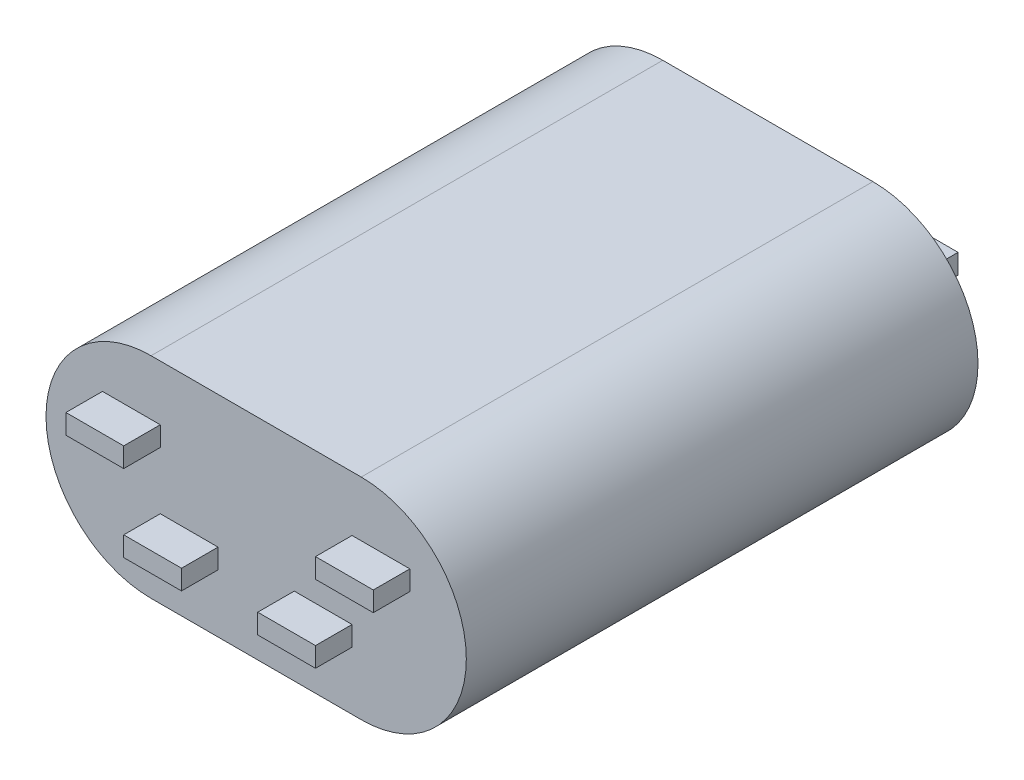
SolidWorks part; units mm, degrees
material "Cast Carbon Steel"
ref_plane "Front Plane" through (0, 0, 0) normal (0, 0, 1) x (1, 0, 0)
ref_plane "Top Plane" through (0, 0, 0) normal (0, 1, 0) x (1, 0, 0)
ref_plane "Right Plane" through (0, 0, 0) normal (1, 0, 0) x (0, 0, -1)
other "Configuration Table"
sketch "Sketch1" plane through (0, 0, 0) normal (0, 0, 1) x (1, 0, 0)
  line L0 (5.75, 14.5) -> (-5.75, 14.5)
  line L1 (-5.75, 3) -> (5.75, 3)
  arc A0 (-5.75, 14.5) -> (-5.75, 3) centre (-5.75, 8.75) ccw
  arc A1 (5.75, 3) -> (5.75, 14.5) centre (5.75, 8.75) ccw
extrude "Extrude1" add sketch "Sketch1" along normal blind 28 from offset 2
sketch "Sketch2" plane through (0, 14.5, 0) normal (0, 1, 0) x (1, 0, 0)
  line L0 (2.2645, -29.1882) -> (2.2645, -2.6726) construction
  text T0 "3 W MAX" font "Century Gothic" height 3.5
extrude "Cut-Extrude1" [suppressed] cut sketch "Sketch2" against normal blind 0.5
sketch "Sketch4" plane through (0, 0, 2) normal (0, 0, -1) x (-1, 0, 0)
  line L0 (0, 3) -> (0, 14.5) construction
  line L1 (-8.4097, 11.479) -> (-5.2473, 11.479)
  line L2 (-8.4097, 11.479) -> (-8.4097, 10.4015)
  line L3 (-8.4097, 10.4015) -> (-5.2473, 10.4015)
  line L4 (-5.2473, 11.479) -> (-5.2473, 10.4015)
  line L5 (-5.2473, 7.2625) -> (-2.0848, 7.2625)
  line L6 (-5.2473, 7.2625) -> (-5.2473, 6.1849)
  line L7 (-5.2473, 6.1849) -> (-2.0848, 6.1849)
  line L8 (-2.0848, 7.2625) -> (-2.0848, 6.1849)
  line L9 (2.0848, 7.2625) -> (5.2473, 7.2625)
  line L10 (2.0848, 7.2625) -> (2.0848, 6.1849)
  line L11 (2.0848, 6.1849) -> (5.2473, 6.1849)
  line L12 (5.2473, 7.2625) -> (5.2473, 6.1849)
  line L13 (5.2473, 11.479) -> (8.4097, 11.479)
  line L14 (5.2473, 11.479) -> (5.2473, 10.4015)
  line L15 (5.2473, 10.4015) -> (8.4097, 10.4015)
  line L16 (8.4097, 11.479) -> (8.4097, 10.4015)
  line L17 (5.75, 3) -> (-5.75, 3) construction
  line L18 (-5.75, 14.5) -> (5.75, 14.5) construction
extrude "Extrude2" add sketch "Sketch4" along normal blind 2 and the other way offset from surface (30 mm away) 2 other way up to face at (0, 8.75, 30)
